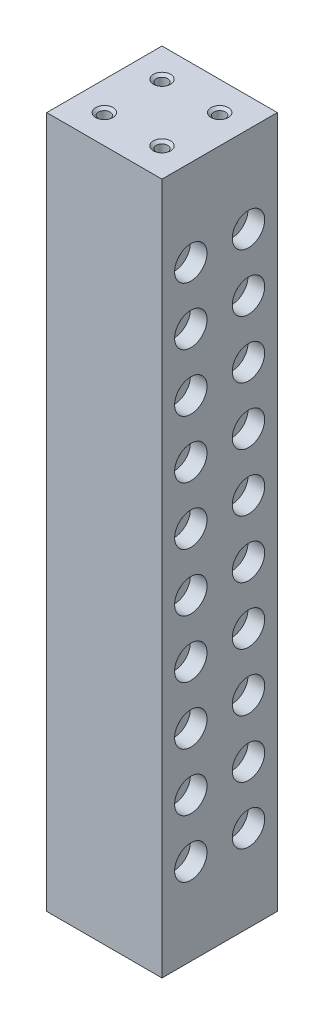
SolidWorks part; units mm, degrees
ref_plane "Front Plane" through (0, 0, 0) normal (0, 0, 1) x (1, 0, 0)
ref_plane "Top Plane" through (0, 0, 0) normal (0, 1, 0) x (1, 0, 0)
ref_plane "Right Plane" through (0, 0, 0) normal (1, 0, 0) x (0, 0, -1)
sketch "Sketch1" plane through (0, 0, 0) normal (0, 1, 0) x (1, 0, 0)
  line L1 (-25.4, -25.4) -> (25.4, -25.4)
  line L2 (-25.4, -25.4) -> (-25.4, 25.4)
  line L3 (-25.4, 25.4) -> (25.4, 25.4)
  line L4 (25.4, -25.4) -> (25.4, 25.4)
  line L5 (0, 25.4) -> (0, -25.4) construction
  line L6 (-25.4, 0) -> (25.4, 0) construction
  point P0 (0, 0)
  dimension "D1" = 50.8
  dimension "D2" = 50.8
extrude "Boss-Extrude1" add sketch "Sketch1" along normal blind 304.8
hole_wizard "1/4-20 Tapped Hole1" positions "Sketch2" profile "Sketch3" tap size "1/4-20" standard "ANSI Inch"
sketch "Sketch2" plane through (0, 304.8, 0) normal (0, 1, 0) x (1, 0, 0)
  point P0 (-12.7, 12.7)
  point P2 (12.7, 12.7)
  point P4 (12.7, -12.7)
  point P6 (-12.7, -12.7)
  point P14 (0, 0)
  point P15 (0, 0)
  point P16 (0, 0)
  point P17 (0, 0)
  point P18 (0, 0)
  point P19 (0, 0)
  dimension "D1" = 12.7
  dimension "D2" = 12.7
  dimension "D3" = 12.7
  dimension "D4" = 12.7
cosmetic thread "Hole Thread1" parameters "D2"=6.35
cosmetic thread "Hole Thread2" parameters "D2"=6.35
cosmetic thread "Hole Thread3" parameters "D2"=6.35
cosmetic thread "Hole Thread4" parameters "D2"=6.35
sketch "Sketch3" plane through (-12.7, 304.8, -12.7) normal (1, 0, 0) x (0, 0, 1)
  line L0 (0, 0) -> (0, 26.9338)
  line L1 (0, 26.9338) -> (2.5527, 25.4)
  line L2 (2.5527, 25.4) -> (2.5527, 1.055)
  line L3 (2.5527, 1.055) -> (3.81, 0)
  line L5 (3.81, 0) -> (0, 0)
  line L6 (-2.5527, 1.055) -> (-3.81, 0) construction
  line L10 (0, 26.9338) -> (-2.5527, 25.4) construction
  line L11 (0, -6.35) -> (0, 107.95) construction
  dimension "Tap Drill Dia." = 5.1054
  dimension "Tap Drill Depth" = 25.4
  dimension "Near C'Sink Dia." = 7.62
  dimension "Near C'Sink Angle" = 100
  dimension "Drill Angle" = 118
ref_plane "Plane1" through (0, 152.4, 0) normal (0, -1, 0) x (-1, 0, 0)
mirror "Mirror1" about plane through (0, 152.4, 0) normal (0, -1, 0) of "1/4-20 Tapped Hole1"
hole_wizard "CBORE for 1/4 Binding Head Machine Screw1" positions "Sketch4" profile "Sketch5" counterbore size "1/4" standard "ANSI Inch" end condition through all
sketch "Sketch4" plane through (25.4, 0, 0) normal (1, 0, 0) x (0, 0, -1)
  line L0 (-25.4, 304.8) -> (-25.4, 0) construction
  line L1 (-25.4, 304.8) -> (25.4, 304.8) construction
  point P0 (-12.7, 266.7)
  point P10 (12.7, 266.7)
  point P11 (12.7, 241.3)
  point P12 (12.7, 215.9)
  point P13 (12.7, 190.5)
  point P14 (-12.7, 241.3)
  point P15 (-12.7, 215.9)
  point P16 (-12.7, 190.5)
  point P19 (-12.7, 165.1)
  point P20 (12.7, 165.1)
  point P21 (-12.7, 139.7)
  point P22 (12.7, 139.7)
  point P23 (-12.7, 114.3)
  point P24 (12.7, 114.3)
  point P25 (-12.7, 88.9)
  point P26 (12.7, 88.9)
  point P27 (-12.7, 63.5)
  point P28 (12.7, 63.5)
  point P29 (-12.7, 38.1)
  point P30 (12.7, 38.1)
  dimension "D1" = 12.7
  dimension "D4" = 38.1
  dimension "D2" = 2
  dimension "D3" = 10
sketch "Sketch5" plane through (25.4, 266.7, 12.7) normal (0, 1, 0) x (0, 0, -1)
  line L0 (0, 0) -> (0, 50.8)
  line L1 (0, 50.8) -> (3.3782, 50.8)
  line L3 (3.3782, 50.8) -> (3.3782, 7.366)
  line L4 (3.3782, 7.366) -> (7.1437, 7.366)
  line L5 (7.1437, 7.366) -> (7.1437, 0)
  line L7 (7.1437, 0) -> (0, 0)
  line L11 (0, -6.35) -> (0, 107.95) construction
  dimension "Thru Hole Dia." = 6.7564
  dimension "Thru Hole Depth" = 50.8
  dimension "C'Bore Dia." = 14.2875
  dimension "C'Bore Depth" = 7.366
